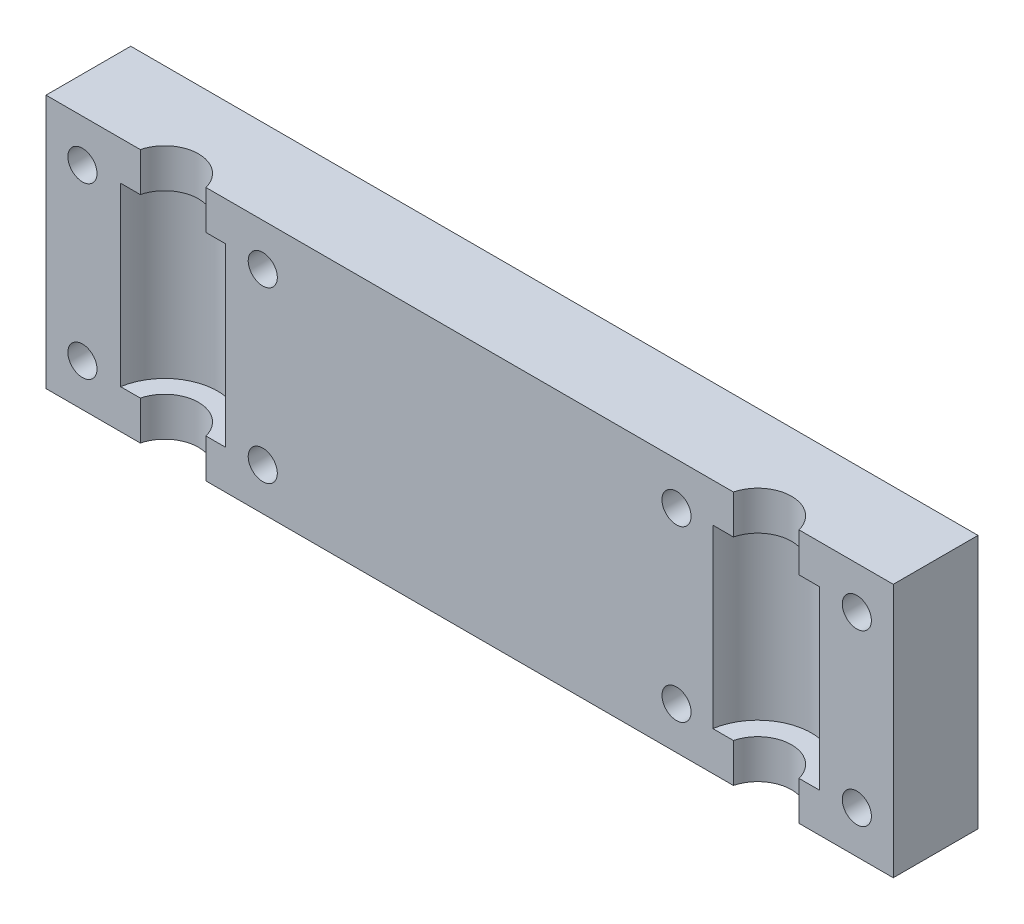
SolidWorks part; units mm, degrees
ref_plane "Front Plane" through (0, 0, 0) normal (0, 0, 1) x (1, 0, 0)
ref_plane "Top Plane" through (0, 0, 0) normal (0, 1, 0) x (1, 0, 0)
ref_plane "Right Plane" through (0, 0, 0) normal (1, 0, 0) x (0, 0, -1)
sketch "Sketch1" plane through (0, 0, 0) normal (0, 1, 0) x (1, 0, 0)
  line L1 (-63.5, 0) -> (63.5, 0)
  line L2 (-63.5, 0) -> (-63.5, -12.7)
  line L3 (-63.5, -12.7) -> (63.5, -12.7)
  line L4 (63.5, 0) -> (63.5, -12.7)
  dimension "D1" = 12.7
  dimension "D2" = 127
  dimension "D3" = 12.7
  dimension "D4" = 63.5
extrude "Boss-Extrude1" add sketch "Sketch1" along normal blind 38.1
sketch "Sketch3" plane through (0, 0, 0) normal (0, 0, -1) x (-1, 0, 0)
  line L0 (-58.039, 38.1) -> (-58.039, 0)
  line L1 (-63.5, 38.1) -> (63.5, 38.1) construction
  line L2 (-63.5, 0) -> (63.5, 0) construction
  line L3 (-63.5, 38.1) -> (-63.5, 0) construction
  line L8 (-44.5241, 38.1) -> (-44.5241, 0)
  line L9 (-31.0092, 38.1) -> (-31.0092, 0)
  line L10 (0, 0) -> (0, 38.1)
  line L11 (31.0092, 38.1) -> (31.0092, 0)
  line L12 (58.039, 38.1) -> (58.039, 0)
  circle A0 centre (-58.039, 31.75) radius 4.445
  circle A1 centre (-58.039, 6.35) radius 4.445
  circle A2 centre (-31.0092, 31.75) radius 4.445
  circle A3 centre (-31.0092, 6.35) radius 4.445
  circle A4 centre (31.0092, 31.75) radius 4.445
  circle A5 centre (31.0092, 6.35) radius 4.445
  circle A6 centre (58.039, 31.75) radius 4.445
  circle A7 centre (58.039, 6.35) radius 4.445
  point P8 (-58.039, 31.75)
  point P9 (-58.039, 6.35)
  point P14 (-31.0092, 6.35)
  point P15 (-31.0092, 31.75)
  point P22 (31.0092, 31.75)
  point P23 (31.0092, 6.35)
  point P24 (58.039, 6.35)
  point P25 (58.039, 31.75)
  dimension "D5" = 8.89
  dimension "D6" = 8.89
  dimension "D7" = 8.89
  dimension "D8" = 8.89
  dimension "D9" = 8.89
  dimension "D10" = 8.89
  dimension "D11" = 8.89
  dimension "D12" = 8.89
  dimension "D1" = 5.461
  dimension "D2" = 6.35
  dimension "D3" = 6.35
  dimension "D4" = 18.9759
extrude "Cut-Extrude3" cut sketch "Sketch3" against normal blind 2.54 contours A2 | A1 | A0 | A6 | A7 | A5 | A4 | A3
ref_plane "Plane2" through (0, 19.05, 0) normal (0, 1, 0) x (1, 0, 0)
sketch "Sketch2" plane through (0, 19.05, 0) normal (0, 1, 0) x (1, 0, 0)
  line L2 (-63.5, 0) -> (-63.5, -12.7) construction
  line L6 (63.5, 0) -> (-63.5, 0) construction
  circle A0 centre (-44.45, -13.97) radius 7.9756
  circle A1 centre (44.45, -13.97) radius 8.1026
  dimension "D1" = 15.9512
  dimension "D4" = 16.2052
  dimension "D2" = 88.9
  dimension "D3" = 19.05
  dimension "D5" = 13.97
  dimension "D6" = 13.97
extrude "Cut-Extrude4" cut sketch "Sketch2" against normal blind 13.208 and the other way blind 13.208
sketch "Sketch6" plane through (0, 38.1, 0) normal (0, 1, 0) x (1, 0, 0)
  circle A0 centre (-44.45, -13.97) radius 5.08
  circle A1 centre (44.45, -13.97) radius 5.08
  dimension "D1" = 10.16
  dimension "D2" = 10.16
extrude "Cut-Extrude5" cut sketch "Sketch6" against normal blind 38.1
hole_wizard "11/64 (0.17188) Diameter Hole1" positions "3DSketch1" profile "Sketch7" hole size "11/64" standard "ANSI Inch"
sketch3d "3DSketch1"
  line L0 (58.039, 31.75, 2.54) -> (58.039, 31.75, 0) construction
  line L1 (58.039, 6.35, 2.54) -> (58.039, 6.35, 0) construction
  line L2 (31.0092, 31.75, 2.54) -> (31.0092, 31.75, 0) construction
  line L3 (31.0092, 6.35, 2.54) -> (31.0092, 6.35, 0) construction
  line L4 (-31.0092, 31.75, 2.54) -> (-31.0092, 31.75, 0) construction
  line L5 (-31.0092, 6.35, 2.54) -> (-31.0092, 6.35, 0) construction
  line L6 (-58.039, 6.35, 2.54) -> (-58.039, 6.35, 0) construction
  line L7 (-58.039, 31.75, 2.54) -> (-58.039, 31.75, 0) construction
  point P0 (58.039, 31.75, 0)
  point P4 (58.039, 6.35, 2.54)
  point P8 (31.0092, 31.75, 0)
  point P12 (31.0092, 6.35, 0)
  point P16 (-31.0092, 31.75, 2.54)
  point P20 (-31.0092, 6.35, 0)
  point P24 (-58.039, 6.35, 2.54)
  point P28 (-58.039, 31.75, 0)
sketch "Sketch7" plane through (58.039, 31.75, 0) normal (1, 0, 0) x (0, 1, 0)
  line L0 (0, 0) -> (0, 26.7116)
  line L1 (0, 26.7116) -> (2.1829, 25.4)
  line L2 (2.1829, 25.4) -> (2.1829, 0)
  line L5 (2.1829, 0) -> (0, 0)
  line L10 (0, 26.7116) -> (-2.1829, 25.4) construction
  line L11 (0, -6.35) -> (0, 107.95) construction
  dimension "Hole Dia." = 4.3658
  dimension "Hole Depth" = 25.4
  dimension "Drill Angle" = 118
